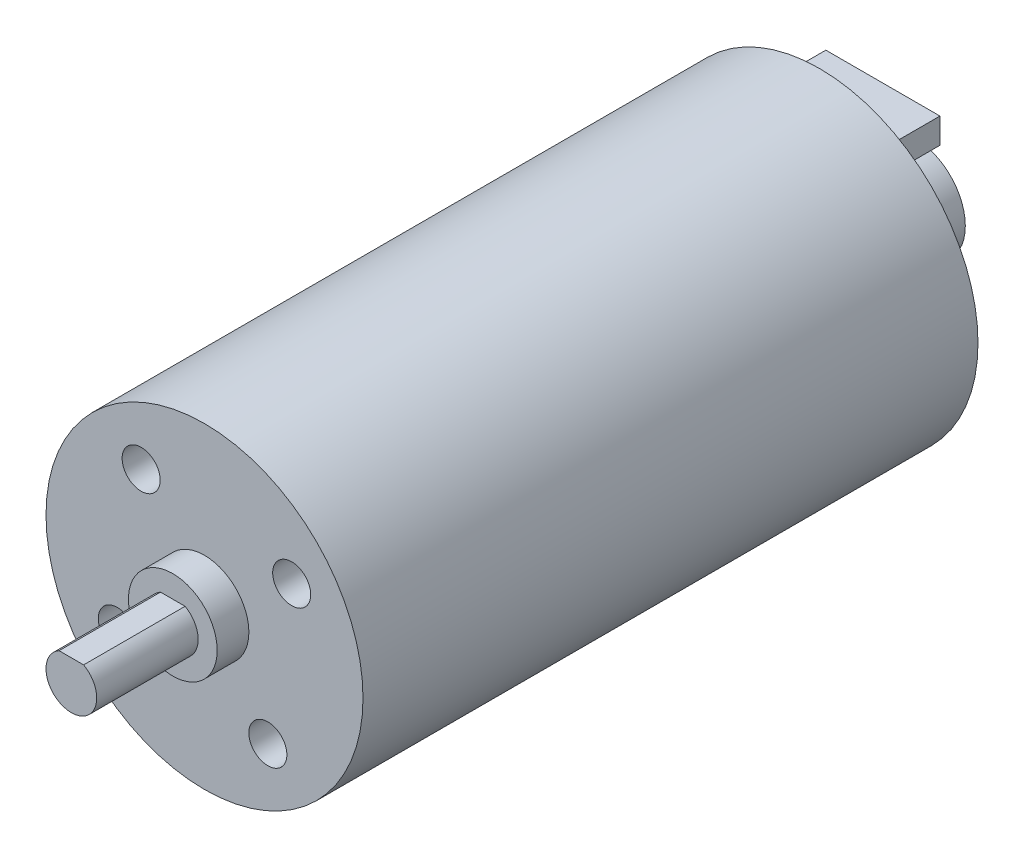
SolidWorks part; units mm, degrees
material "AISI 304"
ref_plane "前视基准面" through (0, 0, 0) normal (0, 0, 1) x (1, 0, 0)
ref_plane "上视基准面" through (0, 0, 0) normal (0, 1, 0) x (1, 0, 0)
ref_plane "右视基准面" through (0, 0, 0) normal (1, 0, 0) x (0, 0, -1)
sketch "草图1" plane through (0, 0, 0) normal (0, 0, 1) x (1, 0, 0)
  circle A0 centre (0, 0) radius 12.5
  dimension "D1" = 25
extrude "凸台-拉伸1" add sketch "草图1" along normal blind 48.5
sketch "草图2" plane through (0, 0, 48.5) normal (0, 0, 1) x (1, 0, 0)
  circle A0 centre (0, 0) radius 3.5
  dimension "D1" = 7
extrude "凸台-拉伸2" add sketch "草图2" along normal blind 2.5
sketch "草图3" plane through (0, 0, 51) normal (0, 0, 1) x (1, 0, 0)
  circle A0 centre (0, 0) radius 2
  dimension "D1" = 4
extrude "凸台-拉伸3" add sketch "草图3" along normal blind 8
sketch "草图4" plane through (0, 0, 59) normal (0, 0, 1) x (1, 0, 0)
  line L1 (-1.7709, 3.0426) -> (1.8164, 3.0426)
  line L2 (-1.7709, 3.0426) -> (-1.7709, 1.7499)
  line L3 (-1.7709, 1.7499) -> (1.8164, 1.7499)
  line L4 (1.8164, 3.0426) -> (1.8164, 1.7499)
  point P4 (0.0227, 1.7499)
  dimension "D1" = 1.75
extrude "切除-拉伸1" cut sketch "草图4" against normal blind 8
sketch "草图5" plane through (0, 0, 48.5) normal (0, 0, 1) x (1, 0, 0)
  circle A0 centre (4.9964, -6.8765) radius 1.5
  circle A1 centre (0, 0) radius 3.5 construction
  circle A2 centre (-6.8765, -4.9964) radius 1.5
  circle A3 centre (-4.9964, 6.8765) radius 1.5
  circle A4 centre (6.8765, 4.9964) radius 1.5
  point P13 (0, 0)
  dimension "D1" = 3
  dimension "D2" = 8.5
  dimension "D3" = 4
extrude "切除-拉伸2" cut sketch "草图5" against normal blind 8
sketch "草图6" plane through (0, 0, 0) normal (0, 0, -1) x (-1, 0, 0)
  circle A0 centre (0, 0) radius 4
  dimension "D1" = 8
extrude "凸台-拉伸4" add sketch "草图6" along normal blind 7.5
sketch "草图7" plane through (0, 0, 0) normal (0, 0, -1) x (-1, 0, 0)
  line L0 (-4.5, 9) -> (4.5, 9)
  line L1 (4.5, -7) -> (-4.5, -7)
  line L2 (4.5, -7) -> (4.5, -9)
  line L3 (4.5, -9) -> (-4.5, -9)
  line L4 (-4.5, -7) -> (-4.5, -9)
  line L5 (-4.5, 7) -> (4.5, 7)
  line L6 (4.5, 7) -> (4.5, 9)
  line L7 (-4.5, 7) -> (-4.5, 9)
  point P13 (0, 0)
  dimension "D1" = 9
  dimension "D2" = 2
  dimension "D3" = 7
  dimension "D4" = 4.5
  dimension "D5" = 2
extrude "凸台-拉伸5" add sketch "草图7" along normal blind 5
